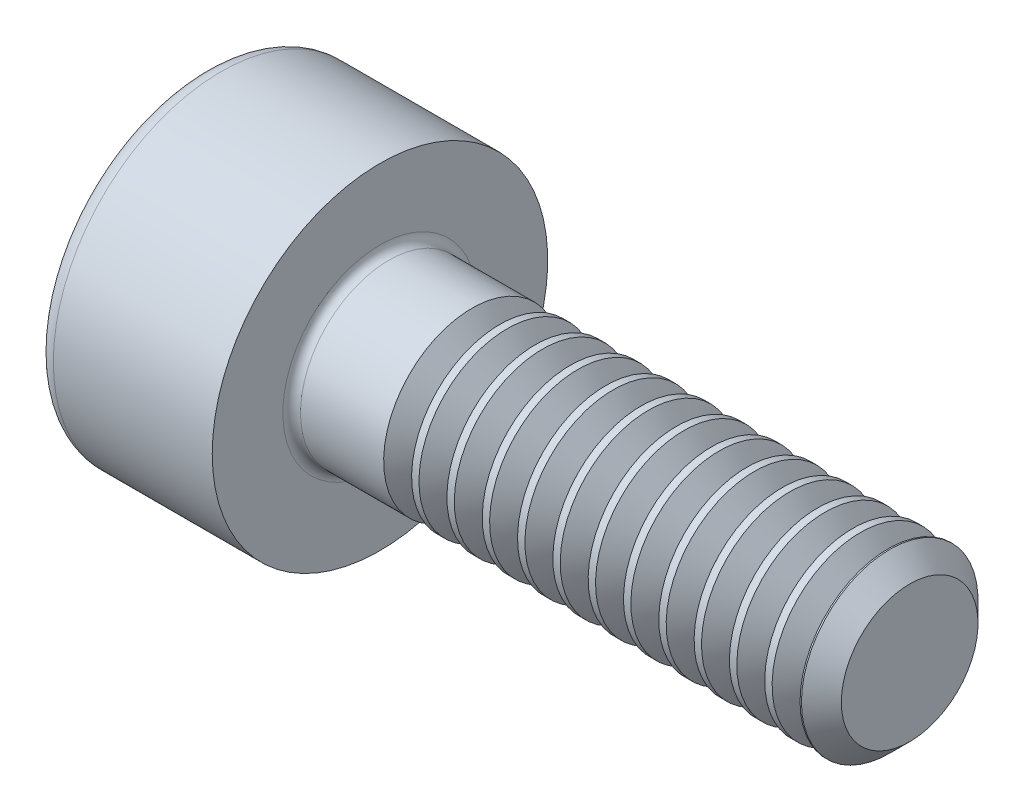
SolidWorks part; units mm, degrees
ref_plane "Plane1" through (0, 0, 0) normal (0, 0, 1) x (1, 0, 0)
ref_plane "Plane2" through (0, 0, 0) normal (0, 1, 0) x (1, 0, 0)
ref_plane "Plane3" through (0, 0, 0) normal (1, 0, 0) x (0, 0, -1)
sketch "BodySke" plane through (0, 0, 0) normal (0, 0, 1) x (1, 0, 0)
  line L0 (0, 0) -> (0, 1.9)
  line L1 (0, 1.9) -> (2, 1.9)
  line L2 (2, 1.9) -> (2, 1)
  line L3 (2, 1) -> (7.774, 1)
  line L4 (8, 0.774) -> (8, 0)
  line L5 (8, 0) -> (0, 0)
  line L6 (-31.75, 0) -> (127, 0) construction
  line L8 (8, 0.774) -> (7.774, 1)
  line L10 (8, -0.774) -> (7.774, -1) construction
  line L11 (2.4, 9.525) -> (2.4, 3.175) construction
  line L12 (2, 9.525) -> (2, 3.175) construction
  line L13 (-52, 9.525) -> (-52, 3.175) construction
  dimension "Diameter" = 2
  dimension "Head_ht" = 2
  dimension "Length" = 6
  dimension "Body_ch_ang" = 45
  dimension "Head_dia" = 3.8
  dimension "Minor_dia" = 1.548
  dimension "Advance" = 0.4
  dimension "Thread_nom" = 6
  dimension "Thread_length" = 60
revolve "Base-Revolve" add sketch "BodySke"
cosmetic thread "ThreadCosmetic" [suppressed]
fillet "Fillet1" radius 0.1 1 edges at (2, 0, 1)
fillet "Fillet2" radius 0.2 1 edges at (0, 0, 1.9)
sketch "Sketch2" plane through (0, 0, 0) normal (0, 0, 1) x (1, 0, 0)
  line L0 (0, 0.76) -> (1, 0.76)
  line L1 (1, 0.76) -> (1.4388, 0)
  line L2 (-31.75, 0) -> (127, 0) construction
  line L3 (1.4388, 0) -> (0, 0)
  line L4 (0, 0) -> (0, 0.76)
  line L6 (0, 0) -> (47.625, 0) construction
  dimension "D1" = 0.76
  dimension "D2" = 60
  dimension "Depth" = 1
revolve "Hex-PreBroach" cut sketch "Sketch2" angle 360 about L6
sketch "Sketch3" plane through (0, 0, 0) normal (-1, 0, 0) x (0, 0.5, 0.866)
  line L0 (0.4388, 0.76) -> (-0.4388, 0.76)
  line L1 (-0.4388, 0.76) -> (-0.8776, 0)
  line L2 (0.4388, 0.76) -> (0.8776, 0)
  line L3 (0.4388, -0.76) -> (0.8776, 0)
  line L4 (0.4388, -0.76) -> (-0.4388, -0.76)
  line L5 (-0.4388, -0.76) -> (-0.8776, 0)
  dimension "D1" = 0.76
  dimension "D2" = 0.76
  dimension "Hex_size" = 1.52
extrude "Hex" cut sketch "Sketch3" against normal blind 1
sketch "ThdSchSke" plane through (0, 0, 0) normal (0, 0, 1) x (1, 0, 0)
  line L0 (3.2, -0.774) -> (3.0418, -1)
  line L1 (3.2, -0.774) -> (3.3582, -1)
  line L2 (3.3582, -1) -> (3.3582, -1.25)
  line L3 (-3.175, 0) -> (5.1513, 0) construction
  line L4 (0, 1.7) -> (0, -1.7) construction
  line L5 (3.3582, -1.25) -> (3.0418, -1.25)
  line L6 (3.0418, -1.25) -> (3.0418, -1)
  dimension "Thread_minor" = 1.548
  dimension "Diameter" = 2
  dimension "Start" = 3.2
  dimension "SideAngle" = 55
  dimension "VeeAngle" = 70
  dimension "Overcut" = 2.5
revolve "ThreadSchematic" cut sketch "ThdSchSke" angle 360 about L3
pattern_linear "ThdSchPat" count 12 spacing 0.4 along (1, 0, 0) of "ThreadSchematic"
equation "\"D2@Sketch3\" = \"Hex_size@Sketch3\" / 2"
equation "\"D1@Sketch3\" = \"Hex_size@Sketch3\" / 2"
equation "\"D1@Sketch2\" = \"Hex_size@Sketch3\" / 2"
equation "\"Thread_minor@ThreadCosmetic\"  =  \"Minor_dia@BodySke\""
equation "\"Depth@Sketch2\" =  \"Key_eng@Hex\""
equation "\"Thread_length@ThreadCosmetic\" = ((sgn( (\"Length@BodySke\" - \"Advance@BodySke\" * 3.0) - \"Thread_nom@BodySke\" )-1)*( (\"Length@BodySke\" - \"Advance@BodySke\" * 3.0) - \"Thread_nom@BodySke\" ))/-2+ \"Thread_nom@BodySke\""
equation "\"Thread_minor@ThdSchSke\" = \"Minor_dia@BodySke\""
equation "\"Diameter@ThdSchSke\" = \"Diameter@BodySke\""
equation "\"Overcut@ThdSchSke\" = \"Diameter@BodySke\" * 1.25"
equation "\"Start@ThdSchSke\" = \"Head_ht@BodySke\" + \"Length@BodySke\" - \"Thread_length@ThreadCosmetic\"  '---Non-countersunk---"
equation "\"Num_threads@ThdSchPat\" = int( \"Thread_length@ThreadCosmetic\" / \"Advance@BodySke\" + 0.999 )  + 1"
equation "\"Advance@ThdSchPat\" = \"Thread_length@ThreadCosmetic\" /  (\"Num_threads@ThdSchPat\" - 1) 'relax it"
equation "\"Num_threads@ThdSchPat\" = \"Num_threads@ThdSchPat\" - sgn( \"Num_threads@ThdSchPat\" - 1) '---chamfered tips only---"
